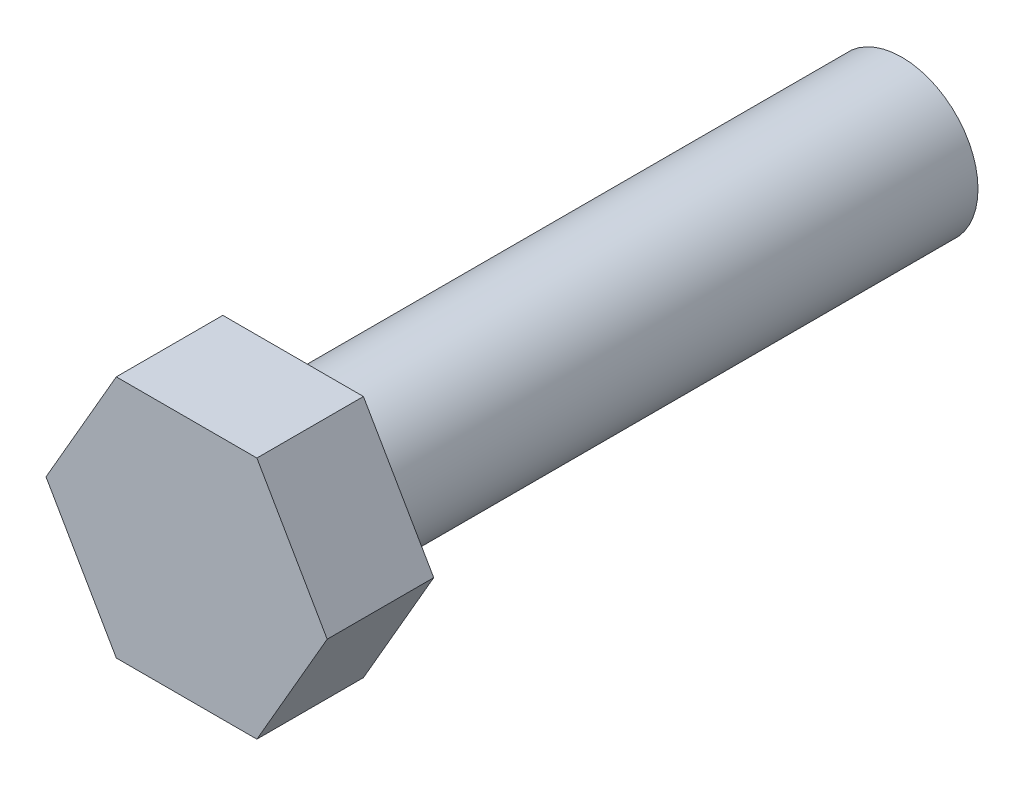
SolidWorks part; units mm, degrees
ref_plane "Alzado" through (0, 0, 0) normal (0, 0, 1) x (1, 0, 0)
ref_plane "Planta" through (0, 0, 0) normal (0, 1, 0) x (1, 0, 0)
ref_plane "Vista lateral" through (0, 0, 0) normal (1, 0, 0) x (0, 0, -1)
sketch "Croquis1" plane through (0, 0, 0) normal (0, 0, 1) x (1, 0, 0)
  line L1 (4.6188, 0) -> (2.3094, 4)
  line L2 (2.3094, 4) -> (-2.3094, 4)
  line L3 (-2.3094, 4) -> (-4.6188, 0)
  line L4 (-4.6188, 0) -> (-2.3094, -4)
  line L5 (-2.3094, -4) -> (2.3094, -4)
  line L6 (2.3094, -4) -> (4.6188, 0)
  circle A0 centre (0, 0) radius 4 construction
  dimension "D1" = 8
extrude "Saliente-Extruir1" add sketch "Croquis1" along normal blind 3.5
sketch "Croquis2" plane through (0, 0, 0) normal (0, 0, -1) x (-1, 0, 0)
  circle A0 centre (0, 0) radius 2.5
  dimension "D1" = 5
extrude "Saliente-Extruir2" add sketch "Croquis2" along normal blind 20
